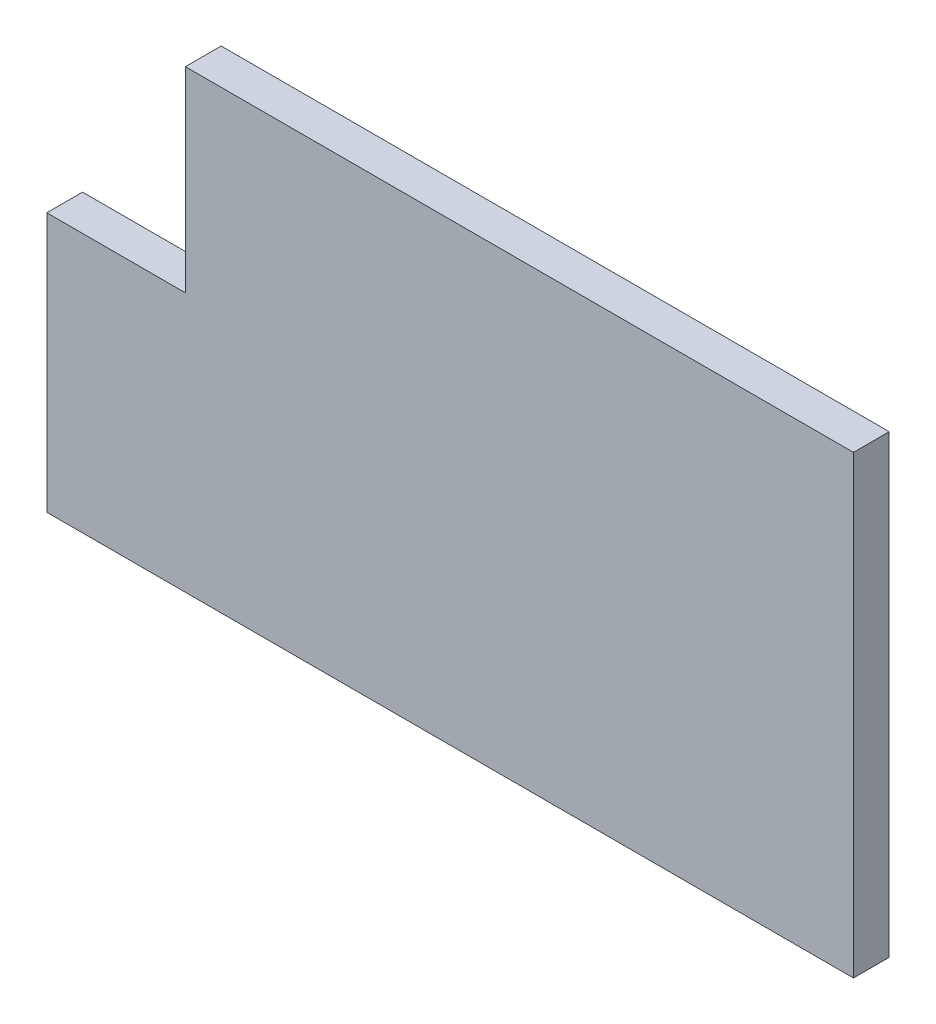
SolidWorks part; units mm, degrees
material "Бетон"
ref_plane "Спереди" through (0, 0, 0) normal (0, 0, 1) x (1, 0, 0)
ref_plane "Сверху" through (0, 0, 0) normal (0, 1, 0) x (1, 0, 0)
ref_plane "Справа" through (0, 0, 0) normal (1, 0, 0) x (0, 0, -1)
sketch "Эскиз1" plane through (0, 0, 0) normal (0, 0, 1) x (1, 0, 0)
  line L9 (906.354, 2129.286) -> (7776.354, 2129.286)
  line L11 (7776.354, 2129.286) -> (8076.354, 2129.286)
  line L12 (8076.354, 2129.286) -> (8076.354, -2660.714)
  line L14 (8076.354, -2660.714) -> (8076.354, -2960.714)
  line L15 (8076.354, -2960.714) -> (-643.646, -2960.714)
  line L17 (-643.646, -2960.714) -> (-943.646, -2960.714)
  line L18 (-943.646, -2960.714) -> (-943.646, -360.714)
  line L20 (906.354, 2129.286) -> (606.354, 2129.286)
  line L21 (606.354, 2129.286) -> (606.354, -60.714)
  line L22 (-943.646, -360.714) -> (-943.646, -60.714)
  line L23 (-943.646, -60.714) -> (606.354, -60.714)
extrude "Бобышка-Вытянуть1" add sketch "Эскиз1" along normal blind 400 contours L21 L23 L22 L18 L17 L15 L14 L12 L11 L9 L20
